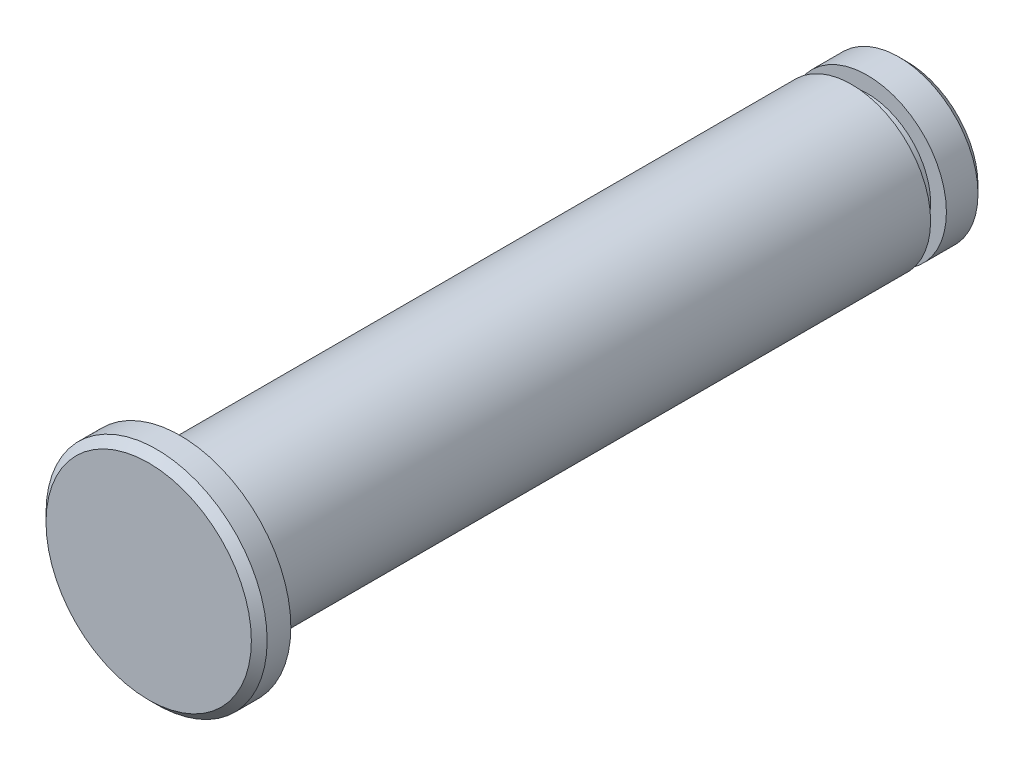
SolidWorks part; units mm, degrees
ref_plane "前视基准面" through (0, 0, 0) normal (0, 0, 1) x (1, 0, 0)
ref_plane "上视基准面" through (0, 0, 0) normal (0, 1, 0) x (1, 0, 0)
ref_plane "右视基准面" through (0, 0, 0) normal (1, 0, 0) x (0, 0, -1)
sketch "草图1" plane through (0, 0, 0) normal (0, 0, 1) x (1, 0, 0)
  circle A0 centre (0, 0) radius 5
  dimension "D1" = 10
extrude "凸台-拉伸1" add sketch "草图1" along normal blind 46
sketch "草图2" plane through (0, 0, 46) normal (0, 0, 1) x (1, 0, 0)
  circle A0 centre (0, 0) radius 7
  dimension "D1" = 14
extrude "凸台-拉伸2" add sketch "草图2" along normal blind 2
chamfer "倒角1" distance 0.5 angle 45 2 edges at (7, 0, 48) (5, 0, 0)
sketch "草图3" plane through (0, 0, 0) normal (0, 0, 1) x (1, 0, 0)
  circle A0 centre (0, 0) radius 4
  dimension "D1" = 8
extrude "切除-拉伸-薄壁1" cut sketch "草图3" along normal blind 1 from offset 2.5 thin
